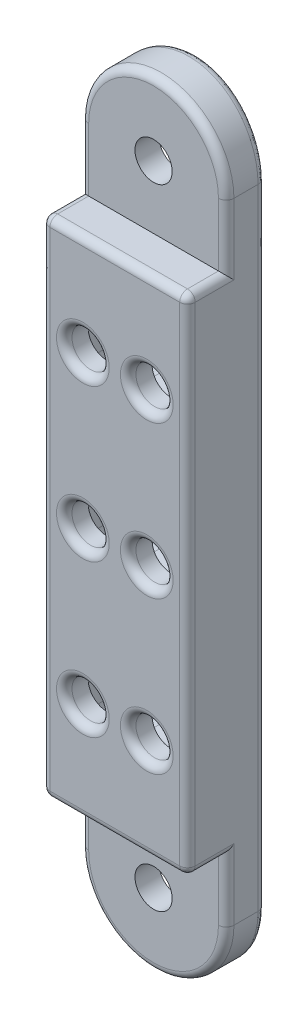
SolidWorks part; units mm, degrees
ref_plane "Front Plane" through (0, 0, 0) normal (0, 0, 1) x (1, 0, 0)
ref_plane "Top Plane" through (0, 0, 0) normal (0, 1, 0) x (1, 0, 0)
ref_plane "Right Plane" through (0, 0, 0) normal (1, 0, 0) x (0, 0, -1)
sketch "Sketch1" plane through (0, 0, 0) normal (0, 1, 0) x (1, 0, 0)
  line L1 (-4.1913, 1.27) -> (5.3337, 1.27)
  line L2 (-4.1913, 1.27) -> (-4.1913, 6.35)
  line L4 (5.3337, 1.27) -> (5.3337, 6.35)
  arc A0 (-4.1913, 6.35) -> (5.3337, 6.35) centre (0.5712, -31.4512) cw
  dimension "D3" = 38.1
  dimension "D1" = 9.525
  dimension "D2" = 5.08
extrude "Main profile" add sketch "Sketch1" along normal blind 50.8
sketch "Sketch2" plane through (0, 0, -1.27) normal (0, 0, 1) x (1, 0, 0)
  line L0 (-4.1913, 50.8) -> (-4.1913, 0) construction
  line L1 (5.3337, 50.8) -> (5.3337, 0) construction
  line L2 (-4.1913, 50.8) -> (5.3337, 50.8) construction
  line L3 (-4.1913, 0) -> (5.3337, 0) construction
  line L4 (-4.1913, 46.0375) -> (-4.1913, 4.7625)
  line L5 (5.3337, 46.0375) -> (5.3337, 4.7625)
  line L10 (-4.1913, 0) -> (5.3337, 0)
  line L11 (5.3337, 0) -> (5.3337, 50.8)
  line L12 (5.3337, 50.8) -> (-4.1913, 50.8)
  line L13 (-4.1913, 50.8) -> (-4.1913, 0)
  line L14 (-4.1913, 0) -> (5.3337, 0)
  line L15 (5.3337, 0) -> (5.3337, 50.8)
  line L16 (5.3337, 50.8) -> (-4.1913, 50.8)
  line L17 (-4.1913, 50.8) -> (-4.1913, 0)
  arc A0 (-4.1913, 46.0375) -> (5.3337, 46.0375) centre (0.5712, 46.0375) cw
  arc A1 (5.3337, 4.7625) -> (-4.1913, 4.7625) centre (0.5712, 4.7625) cw
  line M9 (-4.1913, 0) -> (5.3337, 0)
  line M10 (5.3337, 0) -> (5.3337, 50.8)
  line M11 (5.3337, 50.8) -> (-4.1913, 50.8)
  line M12 (-4.1913, 50.8) -> (-4.1913, 0)
  dimension "D2" = 4.7625
  dimension "D1" = 0
extrude "End rounds" cut sketch "Sketch2" against normal blind 25.4 contours A0 L16 M12 | A0 M11 M10 | A1 L14 M10 | A1 M9 M12
sketch "Sketch3" plane through (-4.1913, 0, 0) normal (-1, 0, 0) x (0, 0, 1)
  line L1 (-1.27, 46.0375) -> (-1.27, 50.8) construction
  line L4 (-1.27, 4.7625) -> (-1.27, 46.0375)
  line L7 (-1.27, 46.0375) -> (-6.35, 46.0375)
  line L8 (-1.27, 4.7625) -> (-1.27, 46.0375)
  line L12 (-1.27, 0) -> (-1.27, 4.7625) construction
  line L14 (-3.81, 25.4) -> (-1.27, 25.4) construction
  line L15 (-1.27, 46.0375) -> (-1.27, 50.8)
  line L17 (-3.81, 41.91) -> (-1.27, 41.91)
  line L18 (-1.27, 0) -> (-1.27, 4.7625)
  line L19 (-1.27, 8.89) -> (-3.81, 8.89)
  line L20 (-2.54, 8.89) -> (-2.54, 41.91) construction
  line L21 (-1.27, 50.8) -> (-3.81, 50.8)
  line L22 (-1.27, 50.8) -> (-1.27, 0)
  line L23 (-1.27, 0) -> (-3.81, 0)
  line L24 (-3.81, 50.8) -> (-3.81, 0)
  line L29 (-6.35, 4.7625) -> (-1.27, 4.7625)
  line L31 (-6.35, 46.0375) -> (-6.35, 4.7625)
  line L32 (-6.35, 46.0375) -> (-6.35, 4.7625)
  spline S0 degree 2 poles (-6.6488, 50.8) (-6.35, 48.4094) (-6.35, 46.0375) knots 0 0 0 0.468627 0.468627 0.468627 weights 0.033338 0.035569 0.037801 construction
  spline S1 degree 2 poles (-6.35, 4.7625) (-6.35, 2.3906) (-6.6488, 0) knots 0.468627 0.468627 0.468627 1 1 1 weights 0.037801 0.040332 0.042863 construction
  spline S2 degree 2 poles (-6.6488, 50.8) (-6.35, 48.4094) (-6.35, 46.0375) knots 0 0 0 0.468627 0.468627 0.468627 weights 0.033338 0.035569 0.037801
  spline S3 degree 2 poles (-6.35, 4.7625) (-6.35, 2.3906) (-6.6488, 0) knots 0.468627 0.468627 0.468627 1 1 1 weights 0.037801 0.040332 0.042863
  point P19 (-2.54, 25.4)
  line M11 (-1.27, 4.7625) -> (-1.27, 46.0375)
  line M12 (-1.27, 46.0375) -> (-6.35, 46.0375)
  line M14 (-6.35, 4.7625) -> (-1.27, 4.7625)
  dimension "D2" = 2.54
  dimension "D3" = 8.89
  dimension "D1" = 0
extrude "Locating Flange" cut sketch "Sketch3" against normal through all contours L24 L23 L18 M14 | L19 L24 M14 M11 | L24 L17 L8 M12 | L21 L24 L15 M12
ref_plane "Top Surface" through (0, 0, -6.6488) normal (0, 0, -1) x (-1, 0, 0)
sketch "Sketch4" plane through (0, 0, -6.6488) normal (0, 0, -1) x (-1, 0, 0)
  line L0 (-0.5712, 18.796) -> (-0.5712, 32.004) construction
  line L1 (-2.3492, 38.735) -> (1.2068, 38.735)
  line L2 (-5.3337, 46.0375) -> (-5.3337, 4.7625)
  line L6 (-3.9367, 37.1475) -> (-3.9367, 33.5915)
  line L7 (-2.3492, 32.004) -> (1.2068, 32.004)
  line L8 (2.7943, 37.1475) -> (2.7943, 33.5915)
  line L9 (-2.3492, 28.7655) -> (1.2068, 28.7655)
  line L14 (-3.9367, 27.178) -> (-3.9367, 23.622)
  line L16 (-2.3492, 22.0345) -> (1.2068, 22.0345)
  line L18 (4.1913, 8.89) -> (4.1913, 41.91)
  line L19 (-5.3337, 8.89) -> (4.1913, 8.89)
  line L20 (-5.3337, 41.91) -> (-5.3337, 8.89)
  line L21 (4.1913, 41.91) -> (-5.3337, 41.91)
  line L22 (4.1913, 8.89) -> (4.1913, 41.91)
  line L23 (-5.3337, 8.89) -> (4.1913, 8.89)
  line L24 (-5.3337, 41.91) -> (-5.3337, 8.89)
  line L25 (4.1913, 41.91) -> (-5.3337, 41.91)
  line L26 (2.7943, 27.178) -> (2.7943, 23.622)
  line L27 (-2.3492, 18.796) -> (1.2068, 18.796)
  line L28 (-3.9367, 17.2085) -> (-3.9367, 13.6525)
  line L29 (-2.3492, 12.065) -> (1.2068, 12.065)
  line L30 (2.7943, 17.2085) -> (2.7943, 13.6525)
  line L31 (-5.3337, 25.4) -> (4.1913, 25.4) construction
  line L34 (-5.3337, 46.0375) -> (-5.3337, 4.7625)
  line L36 (4.1913, 4.7625) -> (4.1913, 46.0375)
  line L37 (4.1913, 4.7625) -> (4.1913, 46.0375)
  arc A0 (1.2068, 12.065) -> (2.7943, 13.6525) centre (1.2068, 13.6525) ccw
  arc A1 (-3.9367, 13.6525) -> (-2.3492, 12.065) centre (-2.3492, 13.6525) ccw
  arc A2 (4.1913, 46.0375) -> (-5.3337, 46.0375) centre (-0.5712, 46.0375) ccw
  arc A3 (4.1913, 46.0375) -> (-5.3337, 46.0375) centre (-0.5712, 46.0375) ccw
  arc A6 (-5.3337, 4.7625) -> (4.1913, 4.7625) centre (-0.5712, 4.7625) ccw
  arc A7 (-5.3337, 4.7625) -> (4.1913, 4.7625) centre (-0.5712, 4.7625) ccw
  arc A8 (1.2068, 18.796) -> (2.7943, 17.2085) centre (1.2068, 17.2085) cw
  arc A9 (-2.3492, 18.796) -> (-3.9367, 17.2085) centre (-2.3492, 17.2085) ccw
  arc A10 (1.2068, 38.735) -> (2.7943, 37.1475) centre (1.2068, 37.1475) cw
  arc A11 (1.2068, 32.004) -> (2.7943, 33.5915) centre (1.2068, 33.5915) ccw
  arc A12 (-3.9367, 33.5915) -> (-2.3492, 32.004) centre (-2.3492, 33.5915) ccw
  arc A13 (1.2068, 22.0345) -> (2.7943, 23.622) centre (1.2068, 23.622) ccw
  arc A14 (-2.3492, 28.7655) -> (-3.9367, 27.178) centre (-2.3492, 27.178) ccw
  arc A15 (-3.9367, 23.622) -> (-2.3492, 22.0345) centre (-2.3492, 23.622) ccw
  arc A16 (1.2068, 28.7655) -> (2.7943, 27.178) centre (1.2068, 27.178) cw
  arc A17 (-2.3492, 38.735) -> (-3.9367, 37.1475) centre (-2.3492, 37.1475) ccw
  point P23 (-0.5712, 18.796)
  point P27 (-0.5712, 25.4)
  point P28 (-0.5712, 28.7655)
  point P57 (-0.5712, 25.4)
  dimension "D6" = 1.5875
  dimension "D4" = 3.175
  dimension "D5" = 3.175
  dimension "D7" = 6.731
  dimension "D1" = 0
  dimension "D3" = 0
extrude "Button Pockets" cut sketch "Sketch4" against normal blind 3.81 contours L16 L0 L9 L14 | L0 L16 L26 L9 | L30 L27 L28 L29 | L6 A12 L7 A11 L8 A10 L1 A17
sketch "Hole Locations" plane through (0, 0, -6.6488) normal (0, 0, -1) x (-1, 0, 0)
  line L2 (-5.3337, 46.0375) -> (-5.3337, 4.7625)
  line L6 (-5.3337, 46.0375) -> (-5.3337, 4.7625)
  line L8 (4.1913, 4.7625) -> (4.1913, 46.0375)
  line L9 (4.1913, 4.7625) -> (4.1913, 46.0375)
  arc A2 (4.1913, 46.0375) -> (-5.3337, 46.0375) centre (-0.5712, 46.0375) ccw
  arc A3 (-5.3337, 4.7625) -> (4.1913, 4.7625) centre (-0.5712, 4.7625) ccw
  arc A4 (4.1913, 46.0375) -> (-5.3337, 46.0375) centre (-0.5712, 46.0375) ccw
  arc A5 (-5.3337, 4.7625) -> (4.1913, 4.7625) centre (-0.5712, 4.7625) ccw
  point P5 (-0.5712, 46.0375)
  point P8 (-0.5712, 4.7625)
  dimension "D1" = 0
hole_wizard "CBORE for #2 Binding Head Machine Screw1" positions "Sketch7" profile "Sketch9" counterbore size "#2" standard "ANSI Inch" end condition through all
sketch "Sketch7" plane through (0, 0, -6.6488) normal (0, 0, -1) x (-1, 0, 0)
  point P0 (-0.5712, 46.0375)
  point P3 (-0.5712, 4.7625)
sketch "Sketch9" plane through (0.5712, 46.0375, -6.6488) normal (1, 0, 0) x (0, 1, 0)
  line L0 (0, 0) -> (0, 5.3788)
  line L1 (0, 5.3788) -> (1.2192, 5.3788)
  line L3 (1.2192, 5.3788) -> (1.2192, 1.27)
  line L4 (1.2192, 1.27) -> (2.7788, 1.27)
  line L5 (2.7788, 1.27) -> (2.7788, 0)
  line L7 (2.7788, 0) -> (0, 0)
  line L11 (0, -6.35) -> (0, 107.95) construction
  dimension "Thru Hole Dia." = 2.4384
  dimension "Thru Hole Depth" = 5.3788
  dimension "C'Bore Dia." = 5.5575
  dimension "C'Bore Depth" = 1.27
sketch "Sketch13" plane through (0, 0, -1.27) normal (0, 0, 1) x (1, 0, 0)
  line L0 (-1.2068, 18.796) -> (2.3492, 18.796) construction
  line L1 (3.9367, 17.2085) -> (3.9367, 13.6525) construction
  line L2 (2.3492, 12.065) -> (-1.2068, 12.065) construction
  line L3 (-2.7943, 13.6525) -> (-2.7943, 17.2085) construction
  line L4 (-1.2068, 28.7655) -> (2.3492, 28.7655) construction
  line L5 (3.9367, 27.178) -> (3.9367, 23.622) construction
  line L6 (2.3492, 22.0345) -> (-1.2068, 22.0345) construction
  line L7 (-2.7943, 23.622) -> (-2.7943, 27.178) construction
  line L8 (3.9367, 37.1475) -> (3.9367, 33.5915) construction
  line L9 (2.3492, 32.004) -> (-1.2068, 32.004) construction
  line L10 (-2.7943, 33.5915) -> (-2.7943, 37.1475) construction
  line L11 (-1.2068, 38.735) -> (2.3492, 38.735) construction
  line L12 (-4.1913, 41.91) -> (-4.1913, 8.89) construction
  line L13 (-4.1913, 8.89) -> (5.3337, 8.89) construction
  line L14 (5.3337, 8.89) -> (5.3337, 41.91) construction
  line L15 (5.3337, 41.91) -> (-4.1913, 41.91) construction
  line L16 (-1.2068, 18.796) -> (2.3492, 18.796)
  line L17 (3.9367, 17.2085) -> (3.9367, 13.6525)
  line L18 (2.3492, 12.065) -> (-1.2068, 12.065)
  line L19 (-2.7943, 13.6525) -> (-2.7943, 17.2085)
  line L20 (-1.2068, 28.7655) -> (2.3492, 28.7655)
  line L21 (3.9367, 27.178) -> (3.9367, 23.622)
  line L22 (2.3492, 22.0345) -> (-1.2068, 22.0345)
  line L23 (-2.7943, 23.622) -> (-2.7943, 27.178)
  line L24 (3.9367, 37.1475) -> (3.9367, 33.5915)
  line L25 (2.3492, 32.004) -> (-1.2068, 32.004)
  line L26 (-2.7943, 33.5915) -> (-2.7943, 37.1475)
  line L27 (-1.2068, 38.735) -> (2.3492, 38.735)
  line L28 (-4.1913, 41.91) -> (-4.1913, 8.89)
  line L29 (-4.1913, 8.89) -> (5.3337, 8.89)
  line L30 (5.3337, 8.89) -> (5.3337, 41.91)
  line L31 (5.3337, 41.91) -> (-4.1913, 41.91)
  line L32 (-1.5243, 35.3695) -> (2.6667, 35.3695) construction
  arc A0 (3.9367, 17.2085) -> (2.3492, 18.796) centre (2.3492, 17.2085) ccw construction
  arc A1 (2.3492, 12.065) -> (3.9367, 13.6525) centre (2.3492, 13.6525) ccw construction
  arc A2 (-2.7943, 13.6525) -> (-1.2068, 12.065) centre (-1.2068, 13.6525) ccw construction
  arc A3 (-1.2068, 18.796) -> (-2.7943, 17.2085) centre (-1.2068, 17.2085) ccw construction
  arc A4 (-1.2068, 28.7655) -> (-2.7943, 27.178) centre (-1.2068, 27.178) ccw construction
  arc A5 (3.9367, 27.178) -> (2.3492, 28.7655) centre (2.3492, 27.178) ccw construction
  arc A6 (2.3492, 22.0345) -> (3.9367, 23.622) centre (2.3492, 23.622) ccw construction
  arc A7 (-2.7943, 23.622) -> (-1.2068, 22.0345) centre (-1.2068, 23.622) ccw construction
  arc A8 (3.9367, 37.1475) -> (2.3492, 38.735) centre (2.3492, 37.1475) ccw construction
  arc A9 (2.3492, 32.004) -> (3.9367, 33.5915) centre (2.3492, 33.5915) ccw construction
  arc A10 (-2.7943, 33.5915) -> (-1.2068, 32.004) centre (-1.2068, 33.5915) ccw construction
  arc A11 (-1.2068, 38.735) -> (-2.7943, 37.1475) centre (-1.2068, 37.1475) ccw construction
  arc A12 (3.9367, 17.2085) -> (2.3492, 18.796) centre (2.3492, 17.2085) ccw
  arc A13 (2.3492, 12.065) -> (3.9367, 13.6525) centre (2.3492, 13.6525) ccw
  arc A14 (-2.7943, 13.6525) -> (-1.2068, 12.065) centre (-1.2068, 13.6525) ccw
  arc A15 (-1.2068, 18.796) -> (-2.7943, 17.2085) centre (-1.2068, 17.2085) ccw
  arc A16 (-1.2068, 28.7655) -> (-2.7943, 27.178) centre (-1.2068, 27.178) ccw
  arc A17 (3.9367, 27.178) -> (2.3492, 28.7655) centre (2.3492, 27.178) ccw
  arc A18 (2.3492, 22.0345) -> (3.9367, 23.622) centre (2.3492, 23.622) ccw
  arc A19 (-2.7943, 23.622) -> (-1.2068, 22.0345) centre (-1.2068, 23.622) ccw
  arc A20 (3.9367, 37.1475) -> (2.3492, 38.735) centre (2.3492, 37.1475) ccw
  arc A21 (2.3492, 32.004) -> (3.9367, 33.5915) centre (2.3492, 33.5915) ccw
  arc A22 (-2.7943, 33.5915) -> (-1.2068, 32.004) centre (-1.2068, 33.5915) ccw
  arc A23 (-1.2068, 38.735) -> (-2.7943, 37.1475) centre (-1.2068, 37.1475) ccw
  point P4 (-1.5243, 35.3695)
  point P5 (2.6667, 35.3695)
  point P9 (2.6667, 25.4)
  point P10 (2.6667, 15.4305)
  point P14 (-1.5243, 15.4305)
  point P15 (-1.5243, 25.4)
  point P18 (0.5712, 35.3695)
  point P19 (0.5712, 41.91)
  point P27 (3.9367, 25.4)
  point P37 (3.9367, 15.4305)
  point P39 (3.9367, 35.3695)
  dimension "D1" = 4.191
hole_wizard "#41 (0.096) Diameter Hole1" positions "Sketch14" profile "Sketch16" hole size "#41" standard "ANSI Inch" end condition through all
sketch "Sketch14" plane through (0, 0, -1.27) normal (0, 0, 1) x (1, 0, 0)
  point P0 (-1.5243, 35.3695)
  point P3 (2.6667, 35.3695)
  point P6 (2.6667, 25.4)
  point P9 (-1.5243, 25.4)
  point P12 (-1.5243, 15.4305)
  point P15 (2.6667, 15.4305)
sketch "Sketch16" plane through (-1.5243, 35.3695, -1.27) normal (1, 0, 0) x (0, -1, 0)
  line L0 (0, 0) -> (0, 5.3788)
  line L1 (0, 5.3788) -> (1.2192, 5.3788)
  line L2 (1.2192, 5.3788) -> (1.2192, 0)
  line L5 (1.2192, 0) -> (0, 0)
  line L11 (0, -6.35) -> (0, 107.95) construction
  dimension "Thru Hole Dia." = 2.4384
  dimension "Thru Hole Depth" = 5.3788
fillet "Fillet1" radius 0.508 26 edges at (-4.1913, 43.9737, -3.81) (0.5712, 50.8, -3.81) (0.5712, 50.8, -6.6488) (-4.1913, 25.4, -6.35) (0.5712, 0, -6.6488) (-4.1913, 6.8262, -3.81) (0.5712, 0, -3.81) (3.2774, 46.6683, -6.5526) (5.3337, 25.4, -1.27) (5.3337, 41.91, -2.54) (5.3337, 43.9737, -3.81) (5.3337, 25.4, -6.35) (5.3337, 6.8262, -3.81) (5.3337, 8.89, -2.54) (-4.1913, 8.89, -2.54) (-4.1913, 41.91, -2.54) (-0.3051, 15.4305, -1.27) (3.8859, 15.4305, -1.27) (-0.3051, 25.4, -1.27) (3.8859, 25.4, -1.27) (3.8859, 35.3695, -1.27) (-0.3051, 35.3695, -1.27) (0.5712, 41.91, -1.27) (-4.1913, 25.4, -1.27) (0.5712, 8.89, -1.27) (3.2774, 5.3933, -6.5526)
